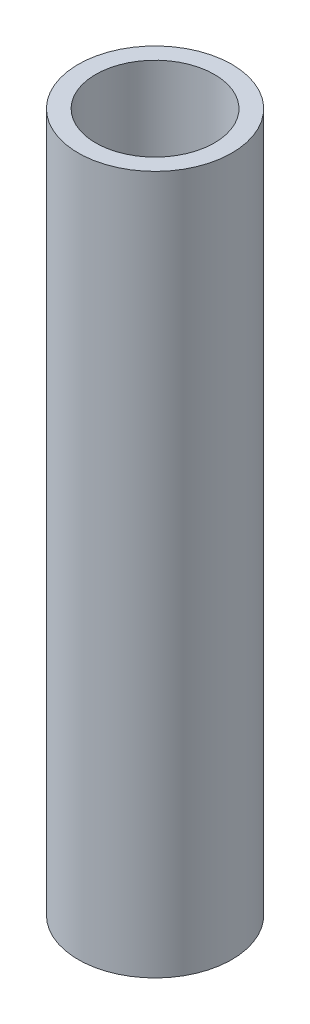
SolidWorks part; units mm, degrees
material "PVC Rigid"
ref_plane "Front Plane" through (0, 0, 0) normal (0, 0, 1) x (1, 0, 0)
ref_plane "Top Plane" through (0, 0, 0) normal (0, 1, 0) x (1, 0, 0)
ref_plane "Right Plane" through (0, 0, 0) normal (1, 0, 0) x (0, 0, -1)
sketch "Sketch1" plane through (0, 0, 0) normal (0, 1, 0) x (1, 0, 0)
  circle A0 centre (0, 0) radius 16.764
  circle A1 centre (0, 0) radius 12.954
extrude "Boss-Extrude1" add sketch "Sketch1" along normal blind 152.4
